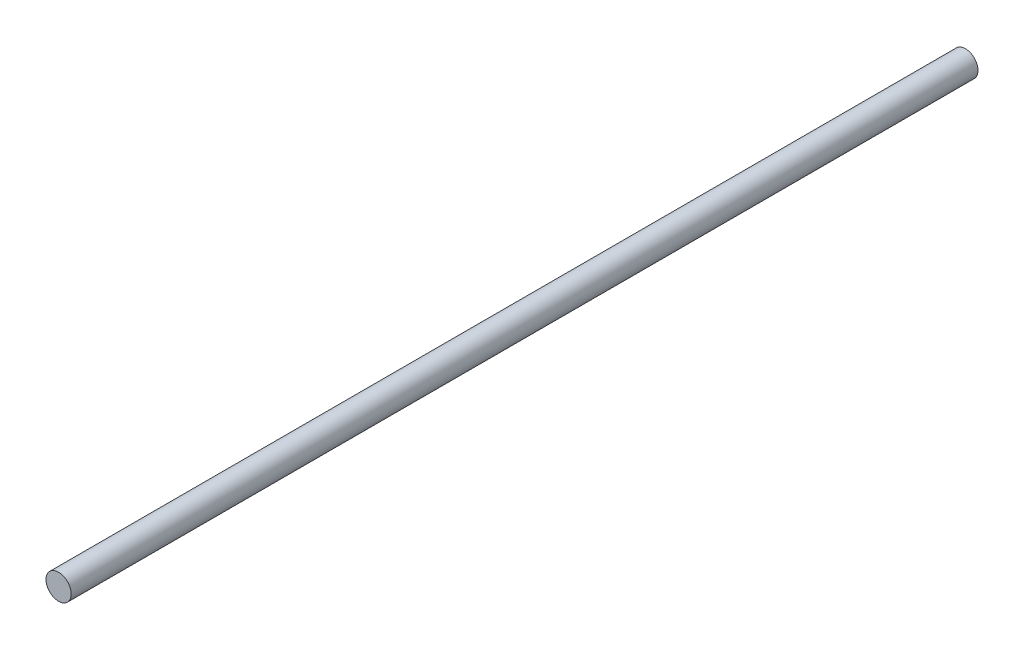
SolidWorks part; units mm, degrees
ref_plane "Front Plane" through (0, 0, 0) normal (0, 0, 1) x (1, 0, 0)
ref_plane "Top Plane" through (0, 0, 0) normal (0, 1, 0) x (1, 0, 0)
ref_plane "Right Plane" through (0, 0, 0) normal (1, 0, 0) x (0, 0, -1)
sketch "Sketch1" plane through (0, 0, 0) normal (0, 1, 0) x (1, 0, 0)
  line L1 (0, 0) -> (1, 0)
  line L2 (0, 0) -> (0, 72)
  line L3 (0, 72) -> (1, 72)
  line L4 (1, 0) -> (1, 72)
  dimension "D1" = 72
  dimension "D2" = 1
revolve "Revolve1" add sketch "Sketch1" angle 360 about L2
